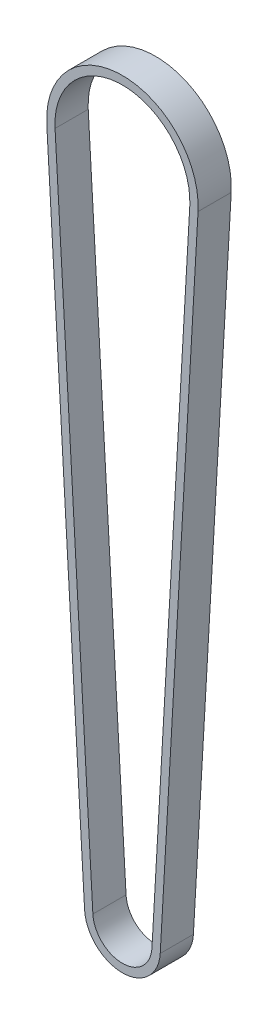
SolidWorks part; units mm, degrees
material "VITON"
ref_plane "Front" through (0, 0, 0) normal (0, 0, 1) x (1, 0, 0)
ref_plane "Top" through (0, 0, 0) normal (0, 1, 0) x (1, 0, 0)
ref_plane "Right" through (0, 0, 0) normal (1, 0, 0) x (0, 0, -1)
sketch "Sketch1" plane through (0, 0, 0) normal (0, 0, 1) x (1, 0, 0)
  line L0 (0, 60) -> (0, -60) construction
  line L1 (-13.6777, 59.218) -> (-6.8388, -60.391)
  line L2 (6.8388, -60.391) -> (13.6777, 59.218)
  arc A0 (-13.6777, 59.218) -> (13.6777, 59.218) centre (0, 60) cw
  arc A1 (-6.8388, -60.391) -> (6.8388, -60.391) centre (0, -60) ccw
  dimension "D1" = 120
  dimension "D2" = 6.85
  dimension "D3" = 13.7
extrude "Extrude-Thin1" add sketch "Sketch1" along normal mid plane 6 thin contours L2 A0 L1 A1 thin type one direction reverse wall 1.5
